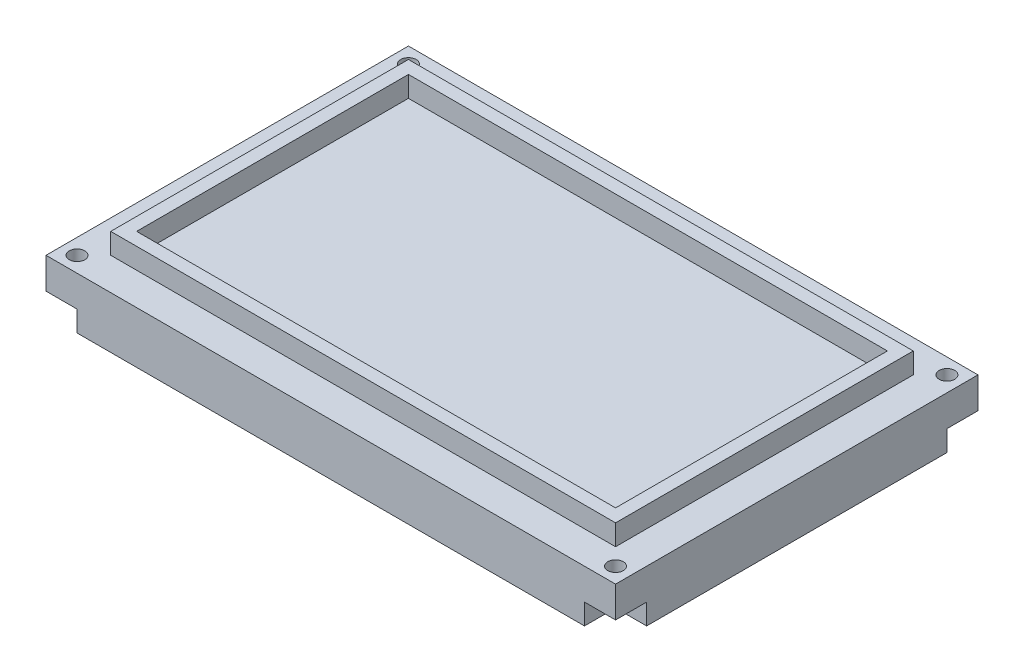
SolidWorks part; units mm, degrees
ref_plane "Front Plane" through (0, 0, 0) normal (0, 0, 1) x (1, 0, 0)
ref_plane "Top Plane" through (0, 0, 0) normal (0, 1, 0) x (1, 0, 0)
ref_plane "Right Plane" through (0, 0, 0) normal (1, 0, 0) x (0, 0, -1)
sketch "Sketch1" plane through (0, 0, 0) normal (0, 1, 0) x (1, 0, 0)
  line L1 (-69.85, 44.45) -> (69.85, 44.45)
  line L2 (-69.85, 44.45) -> (-69.85, -44.45)
  line L3 (-69.85, -44.45) -> (69.85, -44.45)
  line L4 (69.85, 44.45) -> (69.85, -44.45)
  line L5 (-69.85, 44.45) -> (69.85, -44.45) construction
  line L6 (-69.85, -44.45) -> (69.85, 44.45) construction
  point P0 (0, 0)
  dimension "D1" = 139.7
  dimension "D2" = 88.9
extrude "Boss-Extrude1" add sketch "Sketch1" along normal blind 12.7
sketch "Sketch4" plane through (0, 12.7, 0) normal (0, 1, 0) x (1, 0, 0)
  circle A0 centre (-66.04, 40.64) radius 1.905
extrude "Cut-Extrude1" cut sketch "Sketch4" against normal through all
mirror "Mirror1" about plane through (0, 0, 0) normal (1, 0, 0) of "Cut-Extrude1"
mirror "Mirror2" about plane through (0, 0, 0) normal (0, 0, 1) of "Mirror1", "Cut-Extrude1"
sketch "Sketch5" plane through (0, 12.7, 0) normal (0, 1, 0) x (1, 0, 0)
  line L0 (-58.7375, 33.3375) -> (-58.7375, -33.3375)
  line L1 (-58.7375, -33.3375) -> (58.7375, -33.3375)
  line L2 (58.7375, -33.3375) -> (58.7375, 33.3375)
  line L3 (58.7375, 33.3375) -> (-58.7375, 33.3375)
  line L4 (-61.9125, 36.5125) -> (-61.9125, -36.5125)
  line L5 (-61.9125, -36.5125) -> (61.9125, -36.5125)
  line L6 (61.9125, -36.5125) -> (61.9125, 36.5125)
  line L7 (61.9125, 36.5125) -> (-61.9125, 36.5125)
  line L8 (0, -6.985) -> (0, 6.985) construction
  line L9 (-6.985, 0) -> (6.985, 0) construction
  dimension "D1" = 123.825
  dimension "D2" = 73.025
  dimension "D3" = 61.9125
  dimension "D4" = 36.5125
  dimension "D5" = 117.475
  dimension "D6" = 66.675
  dimension "D7" = 33.3375
  dimension "D8" = 58.7375
extrude "Boss-Extrude2" add sketch "Sketch5" along normal blind 5.08
sketch "Sketch6" plane through (0, 0, 0) normal (0, -1, 0) x (1, 0, 0)
  line L0 (-69.85, -44.45) -> (-69.85, 44.45) construction
  line L1 (-69.85, 36.83) -> (-62.23, 36.83)
  line L2 (-62.23, 36.83) -> (-62.23, 44.45)
  line L3 (-69.85, 44.45) -> (69.85, 44.45) construction
  line L4 (-62.23, 44.45) -> (-69.85, 44.45)
  line L5 (-69.85, 44.45) -> (-69.85, 36.83)
  dimension "D1" = 7.62
  dimension "D2" = 7.62
extrude "Cut-Extrude2" cut sketch "Sketch6" against normal blind 5.08
mirror "Mirror3" about plane through (0, 0, 0) normal (1, 0, 0) of "Cut-Extrude2"
mirror "Mirror4" about plane through (0, 0, 0) normal (0, 0, 1) of "Mirror3", "Cut-Extrude2"
